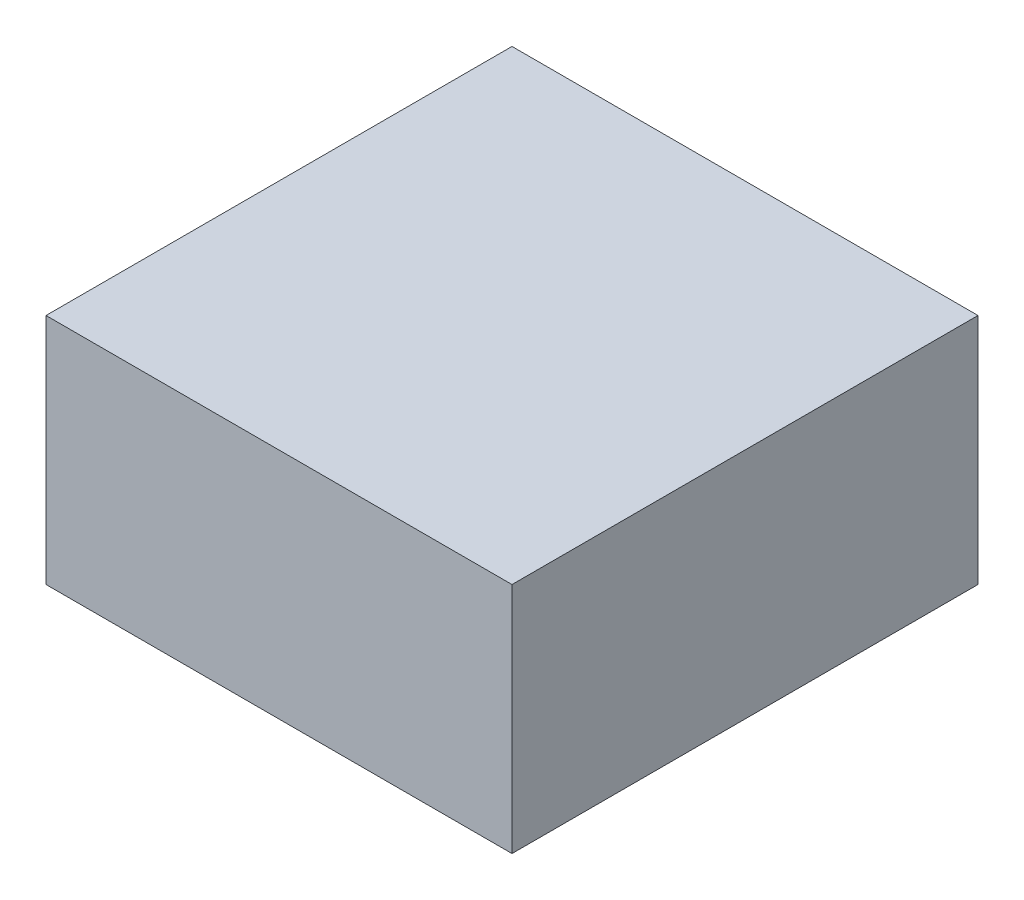
SolidWorks part; units mm, degrees
ref_plane "Front Plane" through (0, 0, 0) normal (0, 0, 1) x (1, 0, 0)
ref_plane "Top Plane" through (0, 0, 0) normal (0, 1, 0) x (1, 0, 0)
ref_plane "Right Plane" through (0, 0, 0) normal (1, 0, 0) x (0, 0, -1)
sketch "Sketch1" plane through (0, 0, 0) normal (0, 1, 0) x (1, 0, 0)
  line L1 (-28, -28) -> (28, -28)
  line L2 (-28, -28) -> (-28, 28)
  line L3 (-28, 28) -> (28, 28)
  line L4 (28, -28) -> (28, 28)
  line L5 (-28, -28) -> (28, 28) construction
  line L6 (-28, 28) -> (28, -28) construction
  point P0 (0, 0)
  dimension "D1" = 56
  dimension "D2" = 56
extrude "Boss-Extrude1" add sketch "Sketch1" along normal blind 28
